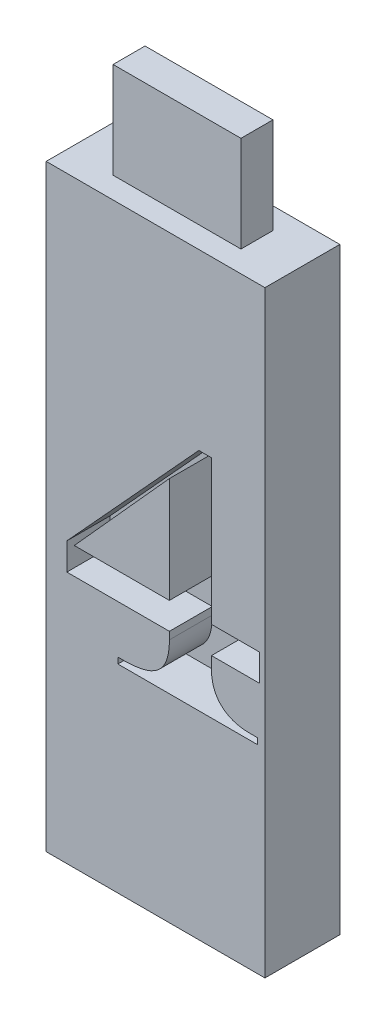
SolidWorks part; units mm, degrees
ref_plane "Front Plane" through (0, 0, 0) normal (0, 0, 1) x (1, 0, 0)
ref_plane "Top Plane" through (0, 0, 0) normal (0, 1, 0) x (1, 0, 0)
ref_plane "Right Plane" through (0, 0, 0) normal (1, 0, 0) x (0, 0, -1)
sketch "Sketch1" plane through (0, 0, 0) normal (0, 0, 1) x (1, 0, 0)
  line L1 (-8.69, -23.749) -> (8.69, -23.749)
  line L2 (-8.69, -23.749) -> (-8.69, 23.749)
  line L3 (-8.69, 23.749) -> (8.69, 23.749)
  line L4 (8.69, -23.749) -> (8.69, 23.749)
  line L5 (-8.69, -23.749) -> (8.69, 23.749) construction
  line L6 (-8.69, 23.749) -> (8.69, -23.749) construction
  point P0 (0, 0)
  dimension "D1" = 17.38
  dimension "D2" = 47.498
extrude "Boss-Extrude1" add sketch "Sketch1" along normal blind 5.95
sketch "Sketch2" plane through (0, 0, 5.95) normal (0, 0, 1) x (1, 0, 0)
  line L0 (0, 23.749) -> (0, -23.749) construction
  line L1 (8.69, 23.749) -> (-8.69, 23.749) construction
  line L2 (-8.69, -23.749) -> (8.69, -23.749) construction
  line L3 (0, -23.749) -> (0, 0) construction
  line L4 (0, 0) -> (-8.69, 0) construction
  line L5 (-8.69, 23.749) -> (-8.69, -23.749) construction
  line L6 (-8.69, 0) -> (8.69, 0) construction
  line L7 (8.69, -23.749) -> (8.69, 23.749) construction
  line L8 (-8.69, -23.749) -> (8.69, -23.749) construction
  line L9 (-8.69, -21.209) -> (8.69, -21.209) construction
  line L10 (-8.69, -18.669) -> (8.69, -18.669) construction
  line L11 (-8.69, -16.129) -> (8.69, -16.129) construction
  line L12 (-8.69, -13.589) -> (8.69, -13.589) construction
  line L13 (-8.69, -11.049) -> (8.69, -11.049) construction
  line L14 (-8.69, -8.509) -> (8.69, -8.509) construction
  line L15 (-8.69, -5.969) -> (8.69, -5.969) construction
  line L16 (-8.69, -3.429) -> (8.69, -3.429) construction
  line L17 (-8.69, -0.889) -> (8.69, -0.889) construction
  line L18 (-8.69, 1.651) -> (8.69, 1.651) construction
  line L19 (-8.69, 4.191) -> (8.69, 4.191) construction
  line L20 (-8.69, 6.731) -> (8.69, 6.731) construction
  line L21 (-8.69, 9.271) -> (8.69, 9.271) construction
  line L22 (-8.69, 11.811) -> (8.69, 11.811) construction
  line L23 (-8.69, 14.351) -> (8.69, 14.351) construction
  line L24 (-8.69, 16.891) -> (8.69, 16.891) construction
  line L25 (-8.69, 19.431) -> (8.69, 19.431) construction
  line L26 (-8.69, 21.971) -> (8.69, 21.971) construction
  line L27 (-8.69, 23.749) -> (-8.69, -23.749) construction
  line L28 (-6.15, 23.749) -> (-6.15, -23.749) construction
  line L29 (-3.61, 23.749) -> (-3.61, -23.749) construction
  line L30 (-1.07, 23.749) -> (-1.07, -23.749) construction
  line L31 (1.47, 23.749) -> (1.47, -23.749) construction
  line L32 (4.01, 23.749) -> (4.01, -23.749) construction
  line L33 (6.55, 23.749) -> (6.55, -23.749) construction
  text T0 "4" font "Engravers MT" height in points 72
  dimension "D1" = 19
  dimension "D2" = 2.54
  dimension "D4" = 2.54
  dimension "D3" = 7
extrude "Cut-Extrude1" cut sketch "Sketch2" against normal blind 3.41
sketch "Sketch3" plane through (0, 23.749, 0) normal (0, 1, 0) x (1, 0, 0)
  line L0 (0, 0) -> (0, -5.95) construction
  line L1 (8.69, -5.95) -> (-8.69, -5.95) construction
  line L2 (0, -5.95) -> (0, -2.975) construction
  line L3 (0, -2.975) -> (-8.69, -2.975) construction
  line L4 (-8.69, -5.95) -> (-8.69, 0) construction
  line L5 (-8.69, -2.975) -> (8.69, -2.975) construction
  line L6 (8.69, -5.95) -> (8.69, 0) construction
  line L8 (-5.08, -4.245) -> (5.08, -4.245)
  line L9 (-5.08, -4.245) -> (-5.08, -1.705)
  line L10 (-5.08, -1.705) -> (5.08, -1.705)
  line L11 (5.08, -4.245) -> (5.08, -1.705)
  line L12 (-5.08, -4.245) -> (5.08, -1.705) construction
  line L13 (-5.08, -1.705) -> (5.08, -4.245) construction
  dimension "D1" = 2.54
  dimension "D2" = 10.16
extrude "Boss-Extrude2" add sketch "Sketch3" along normal blind 7.62
